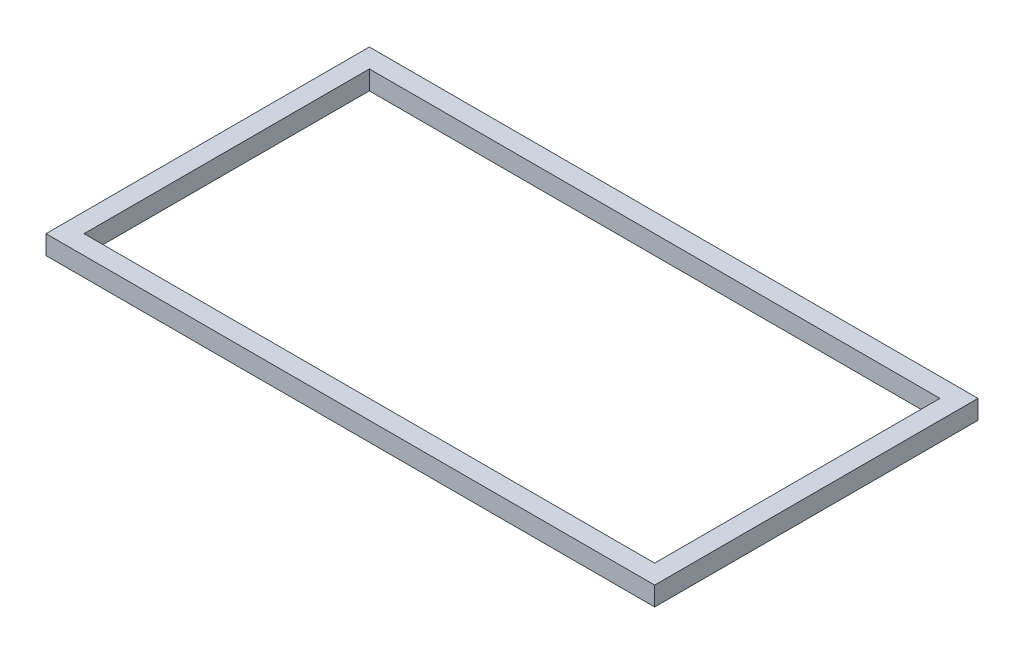
SolidWorks part; units mm, degrees
ref_plane "Front" through (0, 0, 0) normal (0, 0, 1) x (1, 0, 0)
ref_plane "Top" through (0, 0, 0) normal (0, 1, 0) x (1, 0, 0)
ref_plane "Right" through (0, 0, 0) normal (1, 0, 0) x (0, 0, -1)
sketch "Sketch1" plane through (0, 0, 0) normal (0, 1, 0) x (1, 0, 0)
  line L1 (0, 0) -> (812.8, 0)
  line L2 (0, 0) -> (0, 431.8)
  line L3 (0, 431.8) -> (812.8, 431.8)
  line L4 (812.8, 0) -> (812.8, 431.8)
  dimension "D1" = 431.8
  dimension "D2" = 812.8
extrude "Boss-Extrude1" add sketch "Sketch1" along normal blind 25.4
sketch "Sketch2" plane through (0, 25.4, 0) normal (0, 1, 0) x (1, 0, 0)
  line L0 (0, 0) -> (812.8, 0) construction
  line L1 (25.4, 25.4) -> (787.4, 25.4)
  line L2 (25.4, 25.4) -> (25.4, 406.4)
  line L3 (25.4, 406.4) -> (787.4, 406.4)
  line L4 (787.4, 25.4) -> (787.4, 406.4)
  line L5 (0, 431.8) -> (0, 0) construction
  point P4 (25.4, 215.9)
  point P7 (406.4, 25.4)
  dimension "D1" = 381
  dimension "D2" = 762
  dimension "D3" = 215.9
  dimension "D4" = 406.4
extrude "Cut-Extrude1" cut sketch "Sketch2" against normal through all
